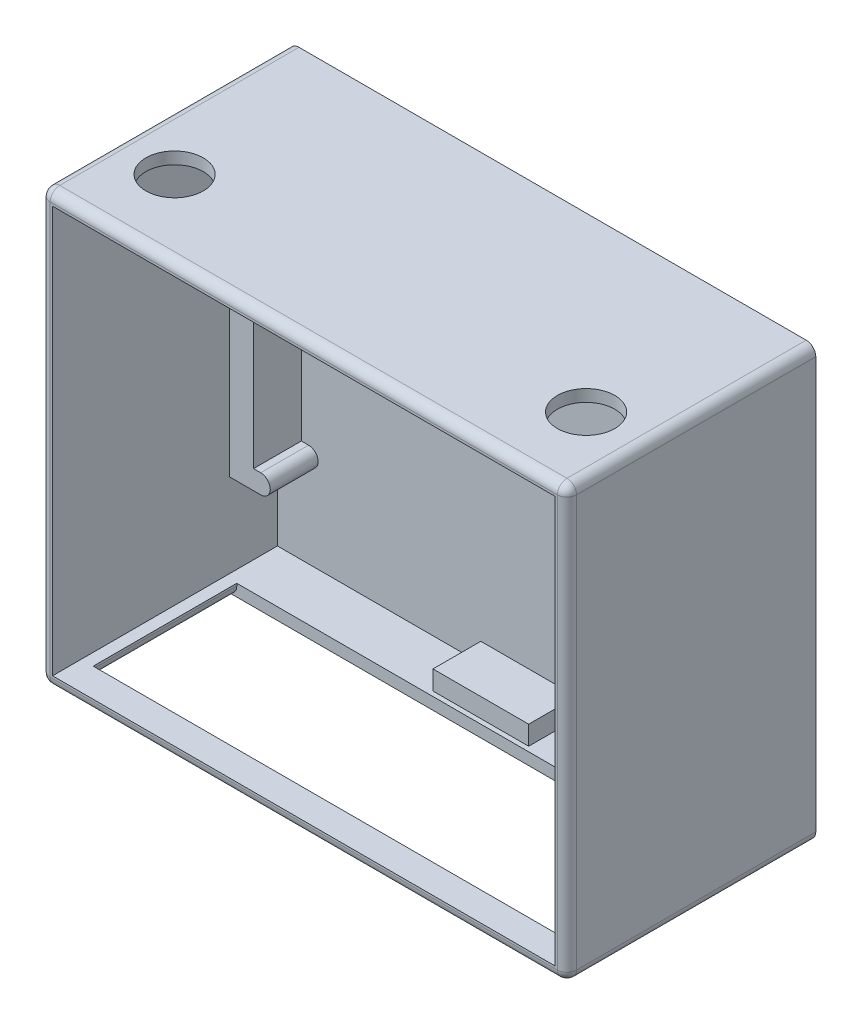
SolidWorks part; units mm, degrees
ref_plane "정면" through (0, 0, 0) normal (0, 0, 1) x (1, 0, 0)
ref_plane "윗면" through (0, 0, 0) normal (0, 1, 0) x (1, 0, 0)
ref_plane "우측면" through (0, 0, 0) normal (1, 0, 0) x (0, 0, -1)
sketch "스케치1" plane through (0, 0, 0) normal (0, 0, 1) x (1, 0, 0)
  line L1 (-55, -45) -> (55, -45)
  line L2 (-55, -45) -> (-55, 45)
  line L3 (-55, 45) -> (55, 45)
  line L4 (55, -45) -> (55, 45)
  line L5 (-55, -45) -> (55, 45) construction
  line L6 (-55, 45) -> (55, -45) construction
  point P0 (0, 0)
  dimension "D1" = 110
  dimension "D2" = 90
extrude "보스-돌출1" add sketch "스케치1" along normal blind 60
sketch "스케치2" plane through (0, 0, 60) normal (0, 0, 1) x (1, 0, 0)
  line L1 (-52.5, -42.5) -> (52.5, -42.5)
  line L2 (-52.5, -42.5) -> (-52.5, 42.5)
  line L3 (-52.5, 42.5) -> (52.5, 42.5)
  line L4 (52.5, -42.5) -> (52.5, 42.5)
  line L5 (-52.5, -42.5) -> (52.5, 42.5) construction
  line L6 (-52.5, 42.5) -> (52.5, -42.5) construction
  point P0 (0, 0)
  dimension "D1" = 105
  dimension "D2" = 85
extrude "컷-돌출1" cut sketch "스케치2" against normal blind 55
sketch "스케치3" plane through (0, -45, 0) normal (0, -1, 0) x (1, 0, 0)
  line L0 (-55, 30) -> (55, 30) construction
  line L1 (-50, 16) -> (50, 16)
  line L2 (-50, 16) -> (-50, 46)
  line L3 (-50, 46) -> (50, 46)
  line L4 (50, 16) -> (50, 46)
  line L5 (-55, 60) -> (55, 60) construction
  line L7 (-55, 60) -> (-55, 0) construction
  line L8 (55, 60) -> (55, 0) construction
  point P11 (0, 0)
  point P12 (0, 0)
  dimension "D1" = 100
  dimension "D2" = 30
  dimension "D3" = 5
  dimension "D4" = 14
extrude "컷-돌출2" cut sketch "스케치3" against normal blind 12
sketch "스케치4" plane through (0, 45, 0) normal (0, 1, 0) x (1, 0, 0)
  line L3 (55, 0) -> (-55, 0) construction
  line L4 (-55, -60) -> (-55, 0) construction
  line L5 (55, -60) -> (55, 0) construction
  circle A0 centre (-43, -36) radius 6
  circle A1 centre (43, -36) radius 6
  point P6 (0, 0)
  dimension "D1" = 12
  dimension "D2" = 12
  dimension "D3" = 36
  dimension "D4" = 12
  dimension "D5" = 12
  dimension "D6" = 36
extrude "컷-돌출3" cut sketch "스케치4" against normal blind 12
ref_plane "평면1" through (0, 0, 10) normal (0, 0, 1) x (1, 0, 0)
sketch "스케치6" plane through (0, 0, 10) normal (0, 0, 1) x (1, 0, 0)
  line L0 (52.5, 42.5) -> (-52.5, 42.5) construction
  line L1 (-10, 42.5) -> (10, 42.5)
  line L2 (-10, 42.5) -> (-10, 38.5)
  line L3 (-10, 38.5) -> (10, 38.5)
  line L4 (10, 42.5) -> (10, 38.5)
  line L5 (52.5, -42.5) -> (52.5, 42.5) construction
  line L6 (52.5, 22.5) -> (47.5, 22.5)
  line L7 (52.5, 22.5) -> (52.5, -22.5)
  line L8 (52.5, -22.5) -> (47.5, -22.5)
  line L9 (47.5, 22.5) -> (47.5, -22.5)
  line L10 (-52.5, -42.5) -> (52.5, -42.5) construction
  line L11 (10, -42.5) -> (-10, -42.5)
  line L12 (10, -42.5) -> (10, -38.5)
  line L13 (10, -38.5) -> (-10, -38.5)
  line L14 (-10, -42.5) -> (-10, -38.5)
  line L15 (-52.5, 42.5) -> (-52.5, -42.5) construction
  line L16 (-52.5, -22.5) -> (-47.5, -22.5)
  line L17 (-52.5, -22.5) -> (-52.5, 22.5)
  line L18 (-52.5, 22.5) -> (-47.5, 22.5)
  line L19 (-47.5, -22.5) -> (-47.5, 22.5)
  line L20 (52.5, 0) -> (-52.5, 0) construction
  line L21 (0, 42.5) -> (0, -42.5) construction
  point P29 (0, 0)
  point P30 (0, 0)
  point P34 (0, 0)
  dimension "D1" = 45
  dimension "D2" = 5
  dimension "D3" = 5
  dimension "D4" = 20
  dimension "D5" = 4
  dimension "D6" = 4
extrude "보스-돌출2" add sketch "스케치6" along normal blind 5 and the other way blind 10
sketch "스케치7" plane through (0, 0, 10) normal (0, 0, 1) x (1, 0, 0)
  line L0 (-46, -21) -> (-50, -21)
  line L1 (-52.5, 42.5) -> (52.5, 42.5) construction
  line L2 (-52.5, 42.5) -> (-52.5, -42.5) construction
  line L3 (-52.5, -42.5) -> (52.5, -42.5) construction
  line L4 (52.5, 42.5) -> (52.5, -42.5) construction
  line L5 (-50, 40) -> (50, 40) construction
  line L6 (-50, 40) -> (-50, -40) construction
  line L7 (-50, -40) -> (50, -40) construction
  line L8 (50, 40) -> (50, -40) construction
  line L9 (0, 40) -> (0, -40) construction
  line L10 (-50, 0) -> (50, 0) construction
  line L11 (-34.5, 38) -> (-34.5, 42.5)
  line L12 (39, 40) -> (50, 40) construction
  line L13 (39, 40) -> (39, 24) construction
  line L14 (39, 24) -> (50, 24) construction
  line L15 (50, 40) -> (50, 24) construction
  line L16 (-40, 40) -> (-32, 40) construction
  line L17 (-40, 40) -> (-40, 36) construction
  line L18 (-40, 36) -> (-32, 36) construction
  line L19 (-32, 40) -> (-32, 36) construction
  line L20 (-37.5, 38) -> (-37.5, 42.5)
  line L21 (-46, -25) -> (-52.5, -25)
  line L22 (-50, -21) -> (-47.5, -22.5)
  line L23 (-47.5, -22.5) -> (-52.5, -22.5)
  line L24 (-52.5, -22.5) -> (-52.5, -25)
  line L25 (42, -24) -> (50, -24)
  line L26 (42, -28) -> (52.5, -28)
  line L27 (52.5, -28) -> (52.5, -22.5)
  line L28 (47.5, -22.5) -> (50, -24)
  line L29 (52.5, -22.5) -> (52.5, 22.5) construction
  line L30 (47.5, -22.5) -> (52.5, -22.5)
  line L31 (44.5, 36) -> (44.5, 42.5)
  line L32 (44.5, 28) -> (52.5, 28)
  line L33 (-37.5, 42.5) -> (-34.5, 42.5)
  line L34 (44.5, 42.5) -> (52.5, 42.5)
  line L35 (52.5, 42.5) -> (52.5, 28)
  arc A0 (-46, -25) -> (-46, -21) centre (-46, -23) ccw
  arc A1 (42, -24) -> (42, -28) centre (42, -26) ccw
  arc A2 (44.5, 36) -> (44.5, 28) centre (44.5, 32) ccw
  arc A3 (-37.5, 38) -> (-34.5, 38) centre (-36, 38) ccw
  dimension "D3" = 4
  dimension "D4" = 4
  dimension "D10" = 8
  dimension "D16" = 8
  dimension "D17" = 3
  dimension "D1" = 100
  dimension "D2" = 80
  dimension "D5" = 17
  dimension "D6" = 4
  dimension "D7" = 14
  dimension "D8" = 8
  dimension "D9" = 8
  dimension "D11" = 5.5
  dimension "D12" = 16
  dimension "D13" = 11
  dimension "D14" = 10
  dimension "D15" = 4
  dimension "D18" = 4
  dimension "D19" = 2
extrude "보스-돌출3" add sketch "스케치7" along normal blind 5 and the other way blind 10
sketch "스케치10" plane through (0, -45, 0) normal (0, -1, 0) x (1, 0, 0)
  line L0 (55, 60) -> (55, 0) construction
  line L1 (-55, 60) -> (55, 60)
  line L2 (-55, 60) -> (-55, 52)
  line L3 (-55, 52) -> (55, 52)
  line L4 (55, 60) -> (55, 52)
  dimension "D1" = 8
extrude "컷-돌출4" cut sketch "스케치10" against normal through all
fillet "필렛1" radius 2 11 edges at (55, 45, 26) (55, -45, 26) (0, -45, 46) (-55, 45, 26) (-55, -45, 26) (-50, -45, 31) (50, -45, 31) (0, -45, 52) (55, 0, 52) (-55, 0, 52) (0, 45, 52)
